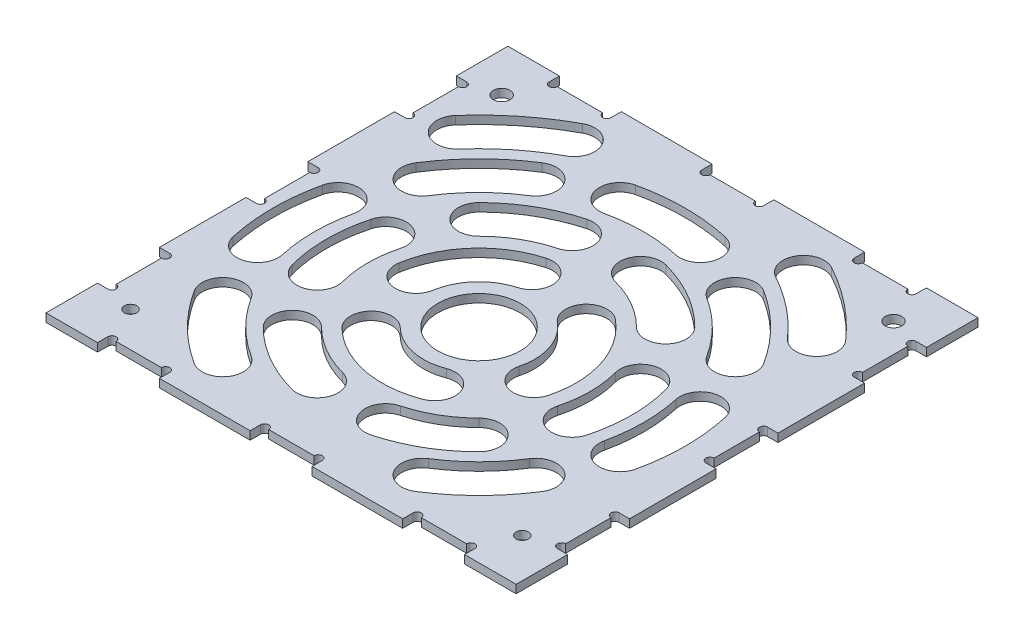
SolidWorks part; units mm, degrees
ref_plane "前视基准面" through (0, 0, 0) normal (0, 0, 1) x (1, 0, 0)
ref_plane "上视基准面" through (0, 0, 0) normal (0, 1, 0) x (1, 0, 0)
ref_plane "右视基准面" through (0, 0, 0) normal (1, 0, 0) x (0, 0, -1)
sketch "草图1" plane through (0, 0, 0) normal (0, 1, 0) x (1, 0, 0)
  line L0 (53, 107) -> (53, 47) construction
  line L1 (0, 0) -> (109, 0)
  line L2 (0, 0) -> (0, 107)
  line L3 (0, 107) -> (109, 107)
  line L4 (109, 0) -> (109, 107)
  line L6 (7, 98.5) -> (102, 98.5) construction
  line L7 (7, 98.5) -> (7, 8.5) construction
  line L8 (7, 8.5) -> (102, 8.5) construction
  line L9 (102, 98.5) -> (102, 8.5) construction
  circle A0 centre (53, 47) radius 13.5 construction
  arc A1 (34.7442, 49.9959) -> (48, 64.8115) centre (53, 47) cw construction
  arc A2 (46.6486, 69.6254) -> (29.8102, 50.8056) centre (53, 47) ccw
  arc A3 (49.3514, 59.9976) -> (39.6782, 49.1862) centre (53, 47) ccw
  arc A4 (49.3514, 59.9976) -> (46.6486, 69.6254) centre (48, 64.8115) ccw
  arc A5 (29.8102, 50.8056) -> (39.6782, 49.1862) centre (34.7442, 49.9959) ccw
  arc A6 (66.0806, 43.661) -> (61.5542, 57.4439) centre (53, 47) ccw
  arc A7 (66.0806, 43.661) -> (75.7699, 41.1877) centre (70.9252, 42.4244) ccw
  arc A8 (67.8907, 65.1801) -> (61.5542, 57.4439) centre (64.7225, 61.312) ccw
  arc A9 (75.7699, 41.1877) -> (67.8907, 65.1801) centre (53, 47) ccw
  arc A10 (64.7225, 61.312) -> (70.9252, 42.4244) centre (53, 47) cw construction
  arc A11 (43.5681, 37.3414) -> (57.7676, 34.3699) centre (53, 47) ccw
  arc A12 (43.5681, 37.3414) -> (36.5815, 30.1869) centre (40.0748, 33.7641) ccw
  arc A13 (61.2991, 25.0142) -> (57.7676, 34.3699) centre (59.5333, 29.692) ccw
  arc A14 (36.5815, 30.1869) -> (61.2991, 25.0142) centre (53, 47) ccw
  arc A15 (59.5333, 29.692) -> (40.0748, 33.7641) centre (53, 47) cw construction
  circle A20 centre (7, 98.5) radius 2
  circle A21 centre (102, 98.5) radius 2
  circle A22 centre (102, 8.5) radius 1.5
  circle A23 centre (7, 8.5) radius 1.5
  point P10 (39.2129, 59.3356)
  point P17 (53, 47)
  point P22 (70.5765, 52.7722)
  point P30 (49.2106, 28.8923)
  point P38 (39.9704, 36.941)
  dimension "D5" = 27
  dimension "D6" = 5
  dimension "D13" = 4
  dimension "D14" = 4
  dimension "D15" = 3
  dimension "D16" = 3
  dimension "D1" = 107
  dimension "D2" = 109
  dimension "D3" = 60
  dimension "D4" = 53
  dimension "D7" = 65
  dimension "D9" = 90
  dimension "D10" = 95
  dimension "D11" = 8.5
  dimension "D12" = 7
  dimension "D8" = 3
extrude "凸台-拉伸1" add sketch "草图1" along normal blind 2
sketch "草图2" plane through (0, 2, 0) normal (0, 1, 0) x (1, 0, 0)
  line L0 (109, 107) -> (0, 107) construction
  line L5 (0, 0) -> (109, 0) construction
  line L6 (0, 107) -> (0, 0) construction
  line L7 (109, 0) -> (109, 107) construction
  line L9 (10, 107) -> (10, 109.5)
  line L11 (25, 107) -> (25, 109.5)
  line L13 (47, 107) -> (47, 109.5)
  line L15 (62, 107) -> (62, 109.5)
  line L17 (84, 107) -> (84, 109.5)
  line L19 (99, 107) -> (99, 109.5)
  line L20 (0, 53.5) -> (109, 53.5) construction
  line L21 (54.5, 0) -> (54.5, 107) construction
  line L22 (109, 97) -> (111.5, 97)
  line L48 (0, 97) -> (-2.5, 97)
  line L49 (10, 107) -> (0, 107)
  line L50 (0, 107) -> (0, 97)
  line L51 (25, 107) -> (47, 107)
  line L52 (62, 107) -> (84, 107)
  line L53 (99, 107) -> (109, 107)
  line L54 (109, 107) -> (109, 97)
  line L67 (10, 109.5) -> (-2.5, 109.5)
  line L68 (-2.5, 109.5) -> (-2.5, 97)
  line L69 (25, 109.5) -> (47, 109.5)
  line L70 (62, 109.5) -> (84, 109.5)
  line L71 (99, 109.5) -> (111.5, 109.5)
  line L72 (111.5, 109.5) -> (111.5, 97)
  line L81 (109, 82) -> (111.5, 82) [skipped]
  line L82 (109, 60) -> (111.5, 60) [skipped]
  line L83 (109, 45) -> (111.5, 45) [skipped]
  line L84 (109, 23) -> (111.5, 23) [skipped]
  line L85 (109, 8) -> (111.5, 8) [skipped]
  line L86 (99, -2) -> (99, -4.5) [skipped]
  line L87 (84, -2) -> (84, -4.5) [skipped]
  line L88 (62, -2) -> (62, -4.5) [skipped]
  line L89 (47, -2) -> (47, -4.5) [skipped]
  line L90 (25, -2) -> (25, -4.5) [skipped]
  line L91 (10, -2) -> (10, -4.5) [skipped]
  line L92 (0, 8) -> (-2.5, 8) [skipped]
  line L93 (0, 23) -> (-2.5, 23) [skipped]
  line L94 (0, 45) -> (-2.5, 45) [skipped]
  line L95 (0, 60) -> (-2.5, 60) [skipped]
  line L96 (0, 82) -> (-2.5, 82) [skipped]
  line L97 (111.5, 46) -> (111.5, 25)
  line L98 (0, 82) -> (-2.5, 82)
  line L99 (0, 82) -> (0, 61)
  line L100 (0, 61) -> (-2.5, 61)
  line L101 (-2.5, 82) -> (-2.5, 61)
  line L102 (0, 46) -> (-2.5, 46)
  line L103 (0, 46) -> (0, 25)
  line L104 (0, 25) -> (-2.5, 25)
  line L105 (-2.5, 46) -> (-2.5, 25)
  line L106 (109, 25) -> (111.5, 25)
  line L107 (109, 46) -> (109, 25)
  line L108 (109, 46) -> (111.5, 46)
  line L109 (111.5, 82) -> (111.5, 61)
  line L110 (109, 61) -> (111.5, 61)
  line L111 (109, 82) -> (109, 61)
  line L112 (109, 82) -> (111.5, 82)
  line L113 (111.5, -2.5) -> (111.5, 10)
  line L114 (99, -2.5) -> (111.5, -2.5)
  line L115 (62, -2.5) -> (84, -2.5)
  line L116 (25, -2.5) -> (47, -2.5)
  line L117 (-2.5, -2.5) -> (-2.5, 10)
  line L118 (10, -2.5) -> (-2.5, -2.5)
  line L119 (109, 0) -> (109, 10)
  line L120 (99, 0) -> (109, 0)
  line L121 (62, 0) -> (84, 0)
  line L122 (25, 0) -> (47, 0)
  line L123 (0, 0) -> (0, 10)
  line L124 (10, 0) -> (0, 0)
  line L125 (0, 10) -> (-2.5, 10)
  line L126 (109, 10) -> (111.5, 10)
  line L127 (99, 0) -> (99, -2.5)
  line L128 (84, 0) -> (84, -2.5)
  line L129 (62, 0) -> (62, -2.5)
  line L130 (47, 0) -> (47, -2.5)
  line L131 (25, 0) -> (25, -2.5)
  line L132 (10, 0) -> (10, -2.5)
  dimension "D2" = 22
  dimension "D3" = 15
  dimension "D4" = 10
  dimension "D5" = 15
  dimension "D6" = 21
  dimension "D7" = 15
  dimension "D8" = 10
  dimension "D9" = 15
  dimension "D10" = 2.5
  dimension "D12" = 15
  dimension "D13" = 21
  dimension "D11" = 4
extrude "凸台-拉伸2" add sketch "草图2" against normal up to surface (2 mm away) up to face at (49.7825, 0, -31.6249)
sketch "草图4" plane through (0, 2, 0) normal (0, 1, 0) x (1, 0, 0)
  line L0 (25, 107) -> (10, 107) construction
  line L1 (10, 107) -> (12, 107)
  line L2 (17.5, 107) -> (17.5, 0) construction
  line L4 (36, 109.5) -> (36, -2.5) construction
  line L5 (0, 53.5) -> (109, 53.5) construction
  line L6 (47, 109.5) -> (25, 109.5) construction
  line L8 (54.5, 107) -> (54.5, 0) construction
  line L9 (62, 107) -> (47, 107) construction
  line L11 (25, 107) -> (23, 107)
  line L12 (47, 107) -> (49, 107)
  line L13 (62, 107) -> (60, 107)
  line L14 (84, 107) -> (86, 107)
  line L15 (99, 107) -> (97, 107)
  line L34 (0, 84) -> (0, 82)
  line L35 (0, 61) -> (0, 46) construction
  line L36 (109, 46) -> (109, 61) construction
  line L37 (99, 0) -> (97, 0)
  line L38 (84, 0) -> (86, 0)
  line L39 (62, 0) -> (60, 0)
  line L40 (47, 0) -> (49, 0)
  line L41 (25, 0) -> (23, 0)
  line L42 (10, 0) -> (12, 0)
  line L43 (0, 95) -> (0, 97)
  line L44 (0, 97) -> (0, 82) construction
  line L45 (0, 89.5) -> (109, 89.5) construction
  line L46 (109, 82) -> (109, 97) construction
  line L47 (-2.5, 71.5) -> (111.5, 71.5) construction
  line L48 (-2.5, 82) -> (-2.5, 61) construction
  line L49 (111.5, 61) -> (111.5, 82) construction
  line L50 (0, 59) -> (0, 61)
  line L51 (0, 48) -> (0, 46)
  line L52 (0, 12) -> (0, 10)
  line L53 (0, 23) -> (0, 25)
  line L54 (109, 23) -> (109, 25)
  line L55 (109, 12) -> (109, 10)
  line L56 (109, 48) -> (109, 46)
  line L57 (109, 59) -> (109, 61)
  line L58 (109, 95) -> (109, 97)
  line L59 (109, 84) -> (109, 82)
  line L60 (10, 0) -> (25, 0) construction
  line L61 (25, -2.5) -> (47, -2.5) construction
  line L62 (47, 0) -> (62, 0) construction
  arc A0 (10, 107) -> (12, 107) centre (11, 107) ccw
  arc A1 (99, 0) -> (97, 0) centre (98, 0) ccw
  arc A2 (25, 107) -> (23, 107) centre (24, 107) cw
  arc A3 (47, 107) -> (49, 107) centre (48, 107) ccw
  arc A4 (62, 107) -> (60, 107) centre (61, 107) cw
  arc A5 (84, 107) -> (86, 107) centre (85, 107) ccw
  arc A6 (99, 107) -> (97, 107) centre (98, 107) cw
  arc A25 (84, 0) -> (86, 0) centre (85, 0) cw
  arc A26 (62, 0) -> (60, 0) centre (61, 0) ccw
  arc A27 (47, 0) -> (49, 0) centre (48, 0) cw
  arc A28 (25, 0) -> (23, 0) centre (24, 0) ccw
  arc A29 (10, 0) -> (12, 0) centre (11, 0) cw
  arc A30 (0, 97) -> (0, 95) centre (0, 96) cw
  arc A31 (0, 82) -> (0, 84) centre (0, 83) ccw
  arc A32 (0, 61) -> (0, 59) centre (0, 60) cw
  arc A33 (0, 46) -> (0, 48) centre (0, 47) ccw
  arc A34 (0, 25) -> (0, 23) centre (0, 24) cw
  arc A35 (0, 10) -> (0, 12) centre (0, 11) ccw
  arc A36 (109, 10) -> (109, 12) centre (109, 11) cw
  arc A37 (109, 25) -> (109, 23) centre (109, 24) ccw
  arc A38 (109, 46) -> (109, 48) centre (109, 47) cw
  arc A39 (109, 61) -> (109, 59) centre (109, 60) ccw
  arc A40 (109, 82) -> (109, 84) centre (109, 83) cw
  arc A41 (109, 97) -> (109, 95) centre (109, 96) ccw
  dimension "D1" = 1
extrude "切除-拉伸1" cut sketch "草图4" against normal through all
sketch "草图5" plane through (0, 2, 0) normal (0, 1, 0) x (1, 0, 0)
  arc A0 (30.3726, 69.6274) -> (44.7178, 77.9096) centre (53, 47) cw construction
  arc A1 (43.4237, 82.7393) -> (26.837, 73.163) centre (53, 47) ccw
  arc A2 (46.0119, 73.08) -> (33.9081, 66.0919) centre (53, 47) ccw
  arc A3 (46.0119, 73.08) -> (43.4237, 82.7393) centre (44.7178, 77.9096) ccw
  arc A4 (26.837, 73.163) -> (33.9081, 66.0919) centre (30.3726, 69.6274) ccw
  circle A5 centre (53, 47) radius 10
  arc A6 (61.2822, 77.9096) -> (75.6274, 69.6274) centre (53, 47) cw construction
  arc A11 (79.163, 73.163) -> (62.5763, 82.7393) centre (53, 47) ccw
  arc A12 (72.0919, 66.0919) -> (59.9881, 73.08) centre (53, 47) ccw
  arc A13 (72.0919, 66.0919) -> (79.163, 73.163) centre (75.6274, 69.6274) ccw
  arc A14 (62.5763, 82.7393) -> (59.9881, 73.08) centre (61.2822, 77.9096) ccw
  arc A15 (83.9096, 55.2822) -> (83.9096, 38.7178) centre (53, 47) cw construction
  arc A16 (88.7393, 37.4237) -> (88.7393, 56.5763) centre (53, 47) ccw
  arc A17 (79.08, 40.0119) -> (79.08, 53.9881) centre (53, 47) ccw
  arc A18 (79.08, 40.0119) -> (88.7393, 37.4237) centre (83.9096, 38.7178) ccw
  arc A19 (88.7393, 56.5763) -> (79.08, 53.9881) centre (83.9096, 55.2822) ccw
  arc A20 (75.6274, 24.3726) -> (61.2822, 16.0904) centre (53, 47) cw construction
  arc A21 (62.5763, 11.2607) -> (79.163, 20.837) centre (53, 47) ccw
  arc A22 (59.9881, 20.92) -> (72.0919, 27.9081) centre (53, 47) ccw
  arc A23 (59.9881, 20.92) -> (62.5763, 11.2607) centre (61.2822, 16.0904) ccw
  arc A24 (79.163, 20.837) -> (72.0919, 27.9081) centre (75.6274, 24.3726) ccw
  arc A25 (44.7178, 16.0904) -> (30.3726, 24.3726) centre (53, 47) cw construction
  arc A26 (26.837, 20.837) -> (43.4237, 11.2607) centre (53, 47) ccw
  arc A27 (33.9081, 27.9081) -> (46.0119, 20.92) centre (53, 47) ccw
  arc A28 (33.9081, 27.9081) -> (26.837, 20.837) centre (30.3726, 24.3726) ccw
  arc A29 (43.4237, 11.2607) -> (46.0119, 20.92) centre (44.7178, 16.0904) ccw
  arc A30 (22.0904, 38.7178) -> (22.0904, 55.2822) centre (53, 47) cw construction
  arc A31 (17.2607, 56.5763) -> (17.2607, 37.4237) centre (53, 47) ccw
  arc A32 (26.92, 53.9881) -> (26.92, 40.0119) centre (53, 47) ccw
  arc A33 (26.92, 53.9881) -> (17.2607, 56.5763) centre (22.0904, 55.2822) ccw
  arc A34 (17.2607, 37.4237) -> (26.92, 40.0119) centre (22.0904, 38.7178) ccw
  arc A35 (15.0474, 71.1785) -> (28.8215, 84.9526) centre (53, 47) cw construction
  arc A36 (26.135, 89.1696) -> (10.8304, 73.865) centre (53, 47) ccw
  arc A37 (31.508, 80.7357) -> (19.2643, 68.492) centre (53, 47) ccw
  arc A38 (31.508, 80.7357) -> (26.135, 89.1696) centre (28.8215, 84.9526) ccw
  arc A39 (10.8304, 73.865) -> (19.2643, 68.492) centre (15.0474, 71.1785) ccw
  arc A40 (61.6576, 86.0518) -> (44.3424, 86.0518) centre (53, 47) ccw
  arc A41 (61.6576, 86.0518) -> (63.822, 95.8148) centre (62.7398, 90.9333) ccw
  arc A42 (42.178, 95.8148) -> (44.3424, 86.0518) centre (43.2602, 90.9333) ccw
  arc A43 (63.822, 95.8148) -> (42.178, 95.8148) centre (53, 47) ccw
  arc A44 (43.2602, 90.9333) -> (62.7398, 90.9333) centre (53, 47) cw construction
  arc A45 (86.7357, 68.492) -> (74.492, 80.7357) centre (53, 47) ccw
  arc A46 (86.7357, 68.492) -> (95.1696, 73.865) centre (90.9526, 71.1785) ccw
  arc A47 (79.865, 89.1696) -> (74.492, 80.7357) centre (77.1785, 84.9526) ccw
  arc A48 (95.1696, 73.865) -> (79.865, 89.1696) centre (53, 47) ccw
  arc A49 (77.1785, 84.9526) -> (90.9526, 71.1785) centre (53, 47) cw construction
  arc A50 (92.0518, 38.3424) -> (92.0518, 55.6576) centre (53, 47) ccw
  arc A51 (92.0518, 38.3424) -> (101.8148, 36.178) centre (96.9333, 37.2602) ccw
  arc A52 (101.8148, 57.822) -> (92.0518, 55.6576) centre (96.9333, 56.7398) ccw
  arc A53 (101.8148, 36.178) -> (101.8148, 57.822) centre (53, 47) ccw
  arc A54 (96.9333, 56.7398) -> (96.9333, 37.2602) centre (53, 47) cw construction
  arc A55 (74.492, 13.2643) -> (86.7357, 25.508) centre (53, 47) ccw
  arc A56 (74.492, 13.2643) -> (79.865, 4.8304) centre (77.1785, 9.0474) ccw
  arc A57 (95.1696, 20.135) -> (86.7357, 25.508) centre (90.9526, 22.8215) ccw
  arc A58 (79.865, 4.8304) -> (95.1696, 20.135) centre (53, 47) ccw
  arc A59 (90.9526, 22.8215) -> (77.1785, 9.0474) centre (53, 47) cw construction
  arc A64 (9.4526, 85.3096) -> (25.1815, 97.8933) centre (53, 47) cw construction
  arc A65 (19.2643, 25.508) -> (31.508, 13.2643) centre (53, 47) ccw
  arc A66 (19.2643, 25.508) -> (10.8304, 20.135) centre (15.0474, 22.8215) ccw
  arc A67 (26.135, 4.8304) -> (31.508, 13.2643) centre (28.8215, 9.0474) ccw
  arc A68 (10.8304, 20.135) -> (26.135, 4.8304) centre (53, 47) ccw
  arc A69 (28.8215, 9.0474) -> (15.0474, 22.8215) centre (53, 47) cw construction
  arc A70 (13.9482, 55.6576) -> (13.9482, 38.3424) centre (53, 47) ccw
  arc A71 (13.9482, 55.6576) -> (4.1852, 57.822) centre (9.0667, 56.7398) ccw
  arc A72 (4.1852, 36.178) -> (13.9482, 38.3424) centre (9.0667, 37.2602) ccw
  arc A73 (4.1852, 57.822) -> (4.1852, 36.178) centre (53, 47) ccw
  arc A74 (9.0667, 37.2602) -> (9.0667, 56.7398) centre (53, 47) cw construction
  arc A75 (22.7833, 102.2807) -> (5.6985, 88.6121) centre (53, 47) ccw
  arc A76 (27.5796, 93.506) -> (13.2067, 82.007) centre (53, 47) ccw
  arc A77 (27.5796, 93.506) -> (22.7833, 102.2807) centre (25.1815, 97.8933) ccw
  arc A78 (5.6985, 88.6121) -> (13.2067, 82.007) centre (9.4526, 85.3096) ccw
  arc A79 (92.7933, 82.007) -> (78.4204, 93.506) centre (53, 47) ccw
  arc A80 (92.7933, 82.007) -> (100.3015, 88.6121) centre (96.5474, 85.3096) ccw
  arc A81 (83.2167, 102.2807) -> (78.4204, 93.506) centre (80.8185, 97.8933) ccw
  arc A82 (100.3015, 88.6121) -> (83.2167, 102.2807) centre (53, 47) ccw
  arc A83 (80.8185, 97.8933) -> (96.5474, 85.3096) centre (53, 47) cw construction
  point P4 (37, 74.7128)
  point P16 (69, 74.7128)
  point P24 (85, 47)
  point P32 (69, 19.2872)
  point P40 (37, 19.2872)
  point P48 (21, 47)
  point P53 (21.1802, 78.8198)
  point P64 (53, 92)
  point P72 (84.8198, 78.8198)
  point P80 (98, 47)
  point P88 (84.8198, 15.1802)
  point P93 (16.7666, 92.2895)
  point P104 (21.1802, 15.1802)
  point P112 (8, 47)
  point P120 (89.2334, 92.2895)
  dimension "D1" = 20
  dimension "D2" = 32
  dimension "D3" = 5
  dimension "D6" = 45
  dimension "D7" = 5
  dimension "D13" = 5
  dimension "D16" = 58
  dimension "D4" = 30
  dimension "D8" = 25
  dimension "D9" = 20
  dimension "D10" = 20
  dimension "D11" = 20
  dimension "D12" = 20
  dimension "D14" = 20
  dimension "D15" = 20
  dimension "D17" = 20
  dimension "D5" = 6
extrude "切除-拉伸2" cut sketch "草图5" against normal through all
